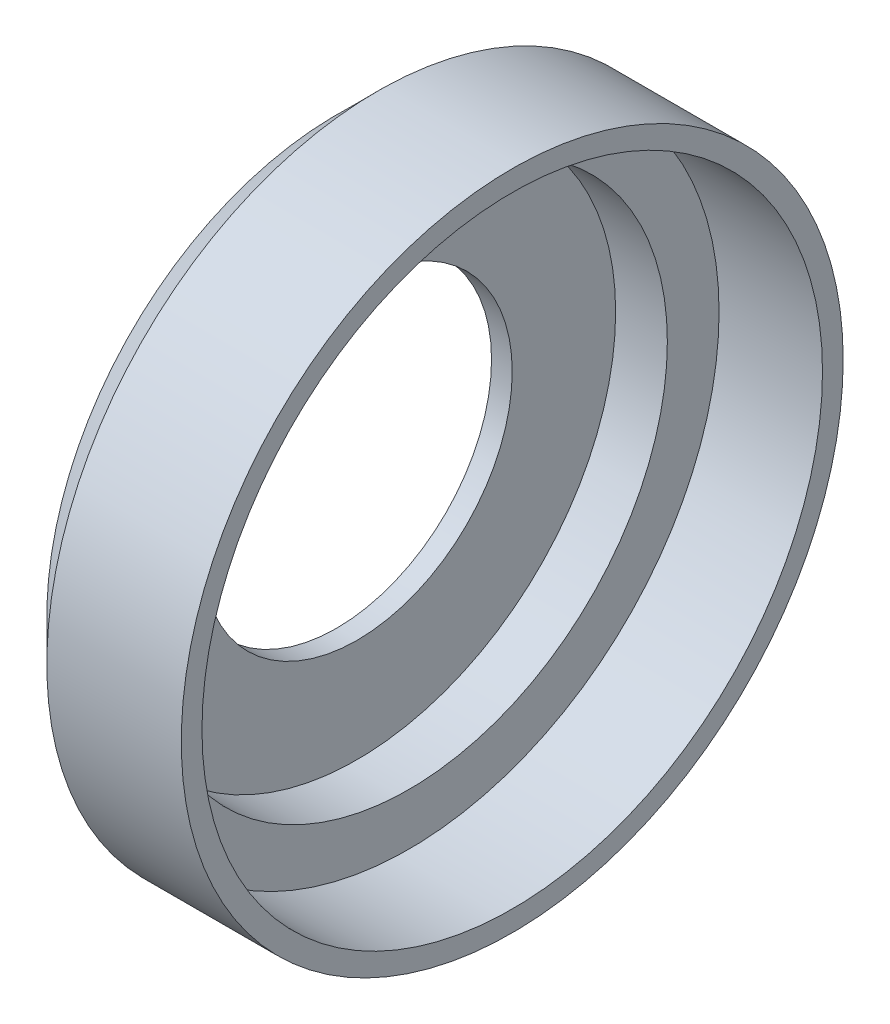
SolidWorks part; units mm, degrees
ref_plane "Front Plane" through (0, 0, 0) normal (0, 0, 1) x (1, 0, 0)
ref_plane "Top Plane" through (0, 0, 0) normal (0, 1, 0) x (1, 0, 0)
ref_plane "Right Plane" through (0, 0, 0) normal (1, 0, 0) x (0, 0, -1)
sketch "Sketch1" plane through (0, 0, 0) normal (0, 1, 0) x (1, 0, 0)
  line L0 (0, 0) -> (-11840.9498, 0) construction
  line L1 (-11.3395, 9.525) -> (-10.0695, 9.525)
  line L2 (-11.3395, 9.525) -> (-11.3395, 17.78)
  line L4 (-10.0695, 9.525) -> (-10.0695, 15.875)
  line L5 (-8.7995, 20.32) -> (-0.5445, 20.32)
  line L7 (-10.0695, 15.875) -> (-6.8945, 15.875)
  line L8 (-6.8945, 19.05) -> (-6.8945, 15.875)
  line L9 (-11.3395, 17.78) -> (-8.7995, 20.32)
  line L12 (-6.8945, 19.05) -> (-0.5445, 19.05)
  line L13 (-0.5445, 20.32) -> (-0.5445, 19.05)
  point P2 (-11.3395, 20.32)
  point P6 (-6.8945, 14.6701)
  point P12 (-11.7676, 20.32)
  point P13 (0, 0)
  point P17 (-0.5445, 19.685)
  point P18 (-7.2052, 13.7771)
  point P19 (-6.2279, 16.1773)
  dimension "D1" = 3.175
  dimension "D2" = 38.1
  dimension "D3" = 19.05
  dimension "D4" = 31.75
  dimension "D5" = 1.27
  dimension "D6" = 1.27
  dimension "D7" = 6.35
revolve "Revolve1" add sketch "Sketch1" angle 360 about L0
